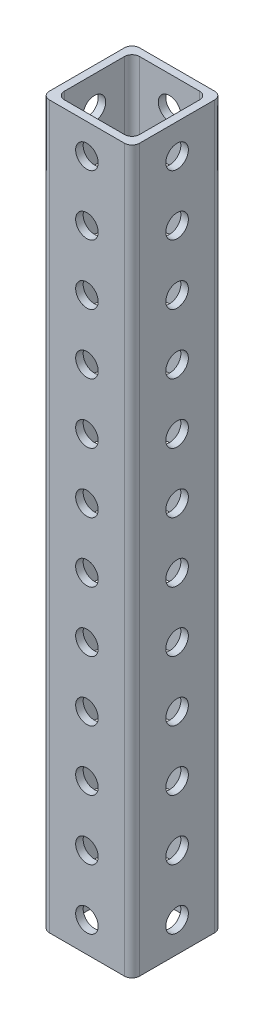
SolidWorks part; units mm, degrees
ref_plane "Front Plane" through (0, 0, 0) normal (0, 0, 1) x (1, 0, 0)
ref_plane "Top Plane" through (0, 0, 0) normal (0, 1, 0) x (1, 0, 0)
ref_plane "Right Plane" through (0, 0, 0) normal (1, 0, 0) x (0, 0, -1)
sketch "Sketch1" plane through (0, 0, 0) normal (0, 1, 0) x (1, 0, 0)
  line L9 (0, 0) -> (38.1, 0)
  line L10 (0, 0) -> (0, 38.1)
  line L11 (0, 38.1) -> (38.1, 38.1)
  line L12 (38.1, 0) -> (38.1, 38.1)
  line L13 (3.175, 3.175) -> (34.925, 3.175)
  line L14 (3.175, 3.175) -> (3.175, 34.925)
  line L15 (3.175, 34.925) -> (34.925, 34.925)
  line L16 (34.925, 3.175) -> (34.925, 34.925)
  dimension "D1" = 38.1
  dimension "D2" = 3.175
  dimension "D3" = 3.175
  dimension "D4" = 3.175
  dimension "D5" = 3.175
extrude "Boss-Extrude1" add sketch "Sketch1" along normal blind 304.8
fillet "Fillet1" radius 3.175 8 edges at (0, 152.4, -38.1) (34.925, 152.4, -3.175) (34.925, 152.4, -34.925) (3.175, 152.4, -3.175) (3.175, 152.4, -34.925) (0, 152.4, 0) (38.1, 152.4, -38.1) (38.1, 152.4, 0)
sketch "Sketch2" plane through (0, 0, 0) normal (0, 0, 1) x (1, 0, 0)
  line L0 (19.05, 304.8) -> (19.05, 0) construction
  line L1 (3.175, 304.8) -> (34.925, 304.8) construction
  line L2 (3.175, 0) -> (34.925, 0) construction
  circle A0 centre (19.05, 12.7) radius 4.7625
  circle A1 centre (19.05, 38.1) radius 4.7625
  circle A2 centre (19.05, 63.5) radius 4.7625
  circle A3 centre (19.05, 88.9) radius 4.7625
  circle A4 centre (19.05, 114.3) radius 4.7625
  circle A5 centre (19.05, 139.7) radius 4.7625
  circle A6 centre (19.05, 165.1) radius 4.7625
  circle A7 centre (19.05, 190.5) radius 4.7625
  circle A8 centre (19.05, 215.9) radius 4.7625
  circle A9 centre (19.05, 241.3) radius 4.7625
  circle A10 centre (19.05, 266.7) radius 4.7625
  circle A11 centre (19.05, 292.1) radius 4.7625
  dimension "D1" = 9.525
  dimension "D3" = 12.7
  dimension "D4" = 12.7
  dimension "D2" = 12
extrude "Cut-Extrude1" cut sketch "Sketch2" against normal through all
sketch "Sketch3" plane through (38.1, 0, 0) normal (1, 0, 0) x (0, 0, -1)
  line L0 (19.05, 304.8) -> (19.05, 0) construction
  line L1 (3.175, 304.8) -> (34.925, 304.8) construction
  line L2 (3.175, 0) -> (34.925, 0) construction
  circle A0 centre (19.05, 12.7) radius 4.7625
  circle A1 centre (19.05, 38.1) radius 4.7625
  circle A2 centre (19.05, 63.5) radius 4.7625
  circle A3 centre (19.05, 88.9) radius 4.7625
  circle A4 centre (19.05, 114.3) radius 4.7625
  circle A5 centre (19.05, 139.7) radius 4.7625
  circle A6 centre (19.05, 165.1) radius 4.7625
  circle A7 centre (19.05, 190.5) radius 4.7625
  circle A8 centre (19.05, 215.9) radius 4.7625
  circle A9 centre (19.05, 241.3) radius 4.7625
  circle A10 centre (19.05, 266.7) radius 4.7625
  circle A11 centre (19.05, 292.1) radius 4.7625
  dimension "D1" = 9.525
  dimension "D2" = 12.7
  dimension "D4" = 38.1
  dimension "D3" = 12
extrude "Cut-Extrude2" cut sketch "Sketch3" against normal through all
